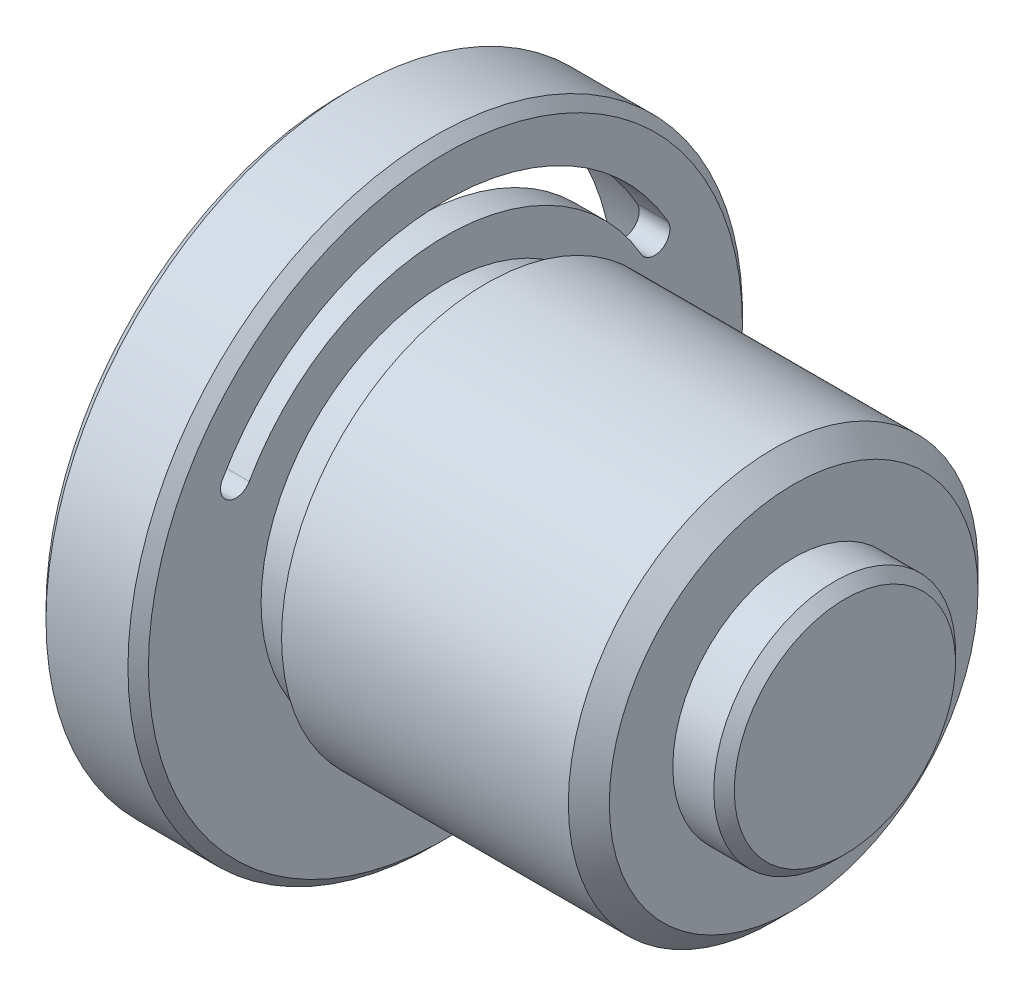
SolidWorks part; units mm, degrees
ref_plane "Plan de face" through (0, 0, 0) normal (0, 0, 1) x (1, 0, 0)
ref_plane "Plan de dessus" through (0, 0, 0) normal (0, 1, 0) x (1, 0, 0)
ref_plane "Plan de droite" through (0, 0, 0) normal (1, 0, 0) x (0, 0, -1)
sketch "Sketch1" plane through (0, 0, 0) normal (0, 0, 1) x (1, 0, 0)
  line L0 (0, 0) -> (0, 5.9)
  line L1 (0, 5.9) -> (-2.5, 5.9)
  line L2 (-2.5, 5.9) -> (-2.5, 10)
  line L3 (-2.5, 10) -> (-17.5, 10)
  line L4 (-17.5, 10) -> (-17.5, 9)
  line L5 (-17.5, 9) -> (-19.5, 9)
  line L6 (-19.5, 9) -> (-19.5, 15)
  line L7 (-19.5, 15) -> (-24.5, 15)
  line L8 (-24.5, 15) -> (-24.5, 13)
  line L9 (-24.5, 0) -> (10.2275, 0) construction
  line L10 (-24.5, 13) -> (-21, 13)
  line L11 (-21, 13) -> (-21, 0)
  line L12 (0, 0) -> (-21, 0)
  dimension "D1" = 5.9
  dimension "D2" = 10
  dimension "D3" = 2
  dimension "D4" = 9
  dimension "D5" = 5
  dimension "D6" = 15
  dimension "D7" = 2.5
  dimension "D8" = 15
  dimension "D9" = 3.5
revolve "Revolve1" add sketch "Sketch1" angle 360 about L9
chamfer "Chamfer1" distance 1 angle 45 1 edges at (-2.5, 0, 10)
chamfer "Chamfer2" distance 0.5 angle 45 1 edges at (0, 0, 5.9)
sketch "Sketch2" plane through (-21, 0, 0) normal (-1, 0, 0) x (0, 0, 1)
  arc A0 (10.8811, 6.1524) -> (-10.8631, 6.1841) centre (0, 0) ccw
  arc A1 (9.5781, 5.4092) -> (-9.56, 5.4412) centre (0, 0) ccw
  arc A3 (10.8811, 6.1524) -> (9.5781, 5.4092) centre (10.2296, 5.7808) cw
  arc A4 (-9.56, 5.4412) -> (-10.8552, 6.198) centre (-10.2076, 5.8196) cw
  dimension "D1" = 25
  dimension "D2" = 22
extrude "Extrude2" cut sketch "Sketch2" against normal blind 10 contours A4 A1 A3 A0
chamfer "Chamfer3" distance 0.5 angle 45 2 edges at (-24.5, 0, 15) (-19.5, 0, 15)
chamfer "Chamfer4" distance 0.2 angle 45 1 edges at (-24.5, 0, 13)
